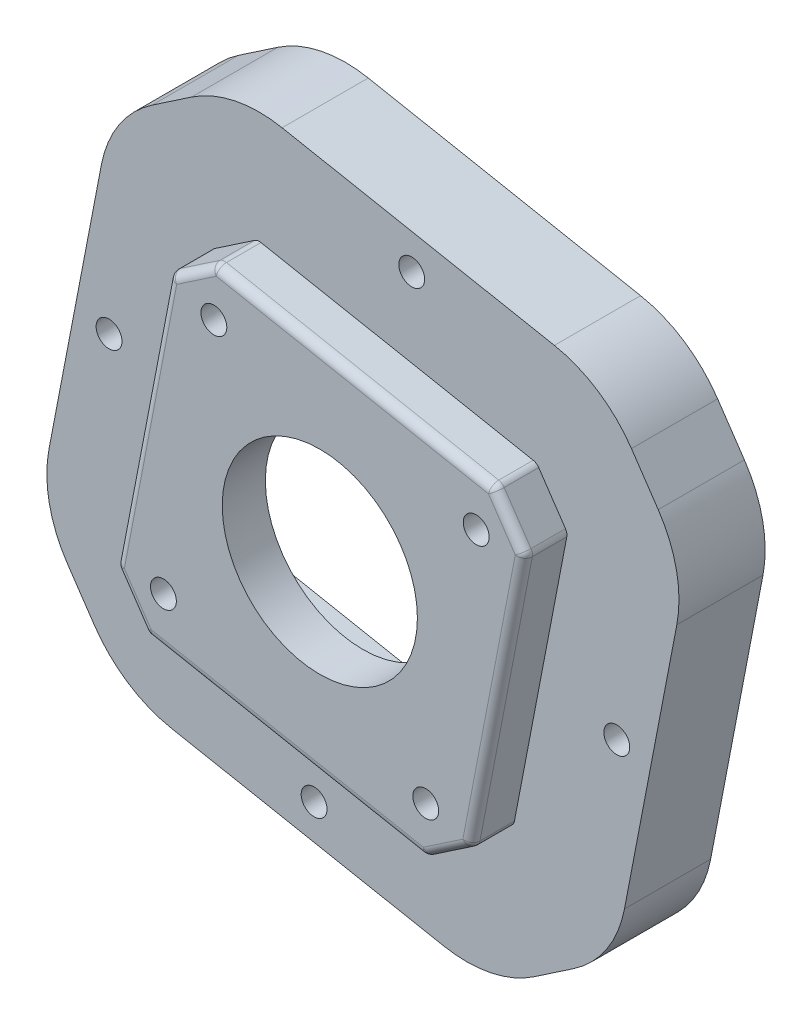
SolidWorks part; units mm, degrees
ref_plane "Plan de face" through (0, 0, 0) normal (0, 0, 1) x (1, 0, 0)
ref_plane "Plan de dessus" through (0, 0, 0) normal (0, 1, 0) x (1, 0, 0)
ref_plane "Plan de droite" through (0, 0, 0) normal (1, 0, 0) x (0, 0, -1)
sketch "Esquisse2" plane through (0, 0, 0) normal (0, 0, 1) x (1, 0, 0)
  line L0 (19.7616, 17.585) -> (-11.8313, 23.6595)
  line L1 (-12.581, 23.5054) -> (-17.1639, 20.4007)
  line L2 (-17.585, 19.7616) -> (-23.6595, -11.8313)
  line L3 (-23.5054, -12.581) -> (-20.4007, -17.1639)
  line L4 (-19.7616, -17.585) -> (11.8313, -23.6595)
  line L5 (12.581, -23.5054) -> (17.1639, -20.4007)
  line L6 (17.585, -19.7616) -> (23.6595, 11.8313)
  line L7 (23.5054, 12.581) -> (20.4007, 17.1639)
  line L8 (30.3512, -22.2162) -> (36.4257, 9.3767)
  line L9 (30.3512, -22.2162) -> (36.4257, 9.3767)
  line L10 (34.2681, 19.8723) -> (31.1634, 24.4552)
  line L11 (34.2681, 19.8723) -> (31.1634, 24.4552)
  line L12 (22.2162, 30.3512) -> (-9.3767, 36.4257)
  line L13 (22.2162, 30.3512) -> (-9.3767, 36.4257)
  line L14 (-19.8723, 34.2681) -> (-24.4552, 31.1634)
  line L15 (-19.8723, 34.2681) -> (-24.4552, 31.1634)
  line L40 (-30.3512, 22.2162) -> (-36.4257, -9.3767)
  line L41 (-30.3512, 22.2162) -> (-36.4257, -9.3767)
  line L42 (-34.2681, -19.8723) -> (-31.1634, -24.4552)
  line L43 (-34.2681, -19.8723) -> (-31.1634, -24.4552)
  line L44 (-22.2162, -30.3512) -> (9.3767, -36.4257)
  line L45 (-22.2162, -30.3512) -> (9.3767, -36.4257)
  line L46 (19.8723, -34.2681) -> (24.4552, -31.1634)
  line L47 (19.8723, -34.2681) -> (24.4552, -31.1634)
  arc A0 (-11.8313, 23.6595) -> (-12.581, 23.5054) centre (-12.0201, 22.6775) ccw
  arc A1 (-17.1639, 20.4007) -> (-17.585, 19.7616) centre (-16.603, 19.5728) ccw
  arc A2 (-23.6595, -11.8313) -> (-23.5054, -12.581) centre (-22.6775, -12.0201) ccw
  arc A3 (-20.4007, -17.1639) -> (-19.7616, -17.585) centre (-19.5728, -16.603) ccw
  arc A4 (11.8313, -23.6595) -> (12.581, -23.5054) centre (12.0201, -22.6775) ccw
  arc A5 (17.1639, -20.4007) -> (17.585, -19.7616) centre (16.603, -19.5728) ccw
  arc A6 (23.6595, 11.8313) -> (23.5054, 12.581) centre (22.6775, 12.0201) ccw
  arc A7 (20.4007, 17.1639) -> (19.7616, 17.585) centre (19.5728, 16.603) ccw
  arc A8 (24.4552, -31.1634) -> (30.3512, -22.2162) centre (16.603, -19.5728) ccw
  arc A9 (24.4552, -31.1634) -> (30.3512, -22.2162) centre (16.603, -19.5728) ccw
  arc A10 (36.4257, 9.3767) -> (34.2681, 19.8723) centre (22.6775, 12.0201) ccw
  arc A11 (36.4257, 9.3767) -> (34.2681, 19.8723) centre (22.6775, 12.0201) ccw
  arc A12 (31.1634, 24.4552) -> (22.2162, 30.3512) centre (19.5728, 16.603) ccw
  arc A13 (31.1634, 24.4552) -> (22.2162, 30.3512) centre (19.5728, 16.603) ccw
  arc A14 (-9.3767, 36.4257) -> (-19.8723, 34.2681) centre (-12.0201, 22.6775) ccw
  arc A15 (-9.3767, 36.4257) -> (-19.8723, 34.2681) centre (-12.0201, 22.6775) ccw
  arc A40 (-24.4552, 31.1634) -> (-30.3512, 22.2162) centre (-16.603, 19.5728) ccw
  arc A41 (-24.4552, 31.1634) -> (-30.3512, 22.2162) centre (-16.603, 19.5728) ccw
  arc A42 (-36.4257, -9.3767) -> (-34.2681, -19.8723) centre (-22.6775, -12.0201) ccw
  arc A43 (-36.4257, -9.3767) -> (-34.2681, -19.8723) centre (-22.6775, -12.0201) ccw
  arc A44 (-31.1634, -24.4552) -> (-22.2162, -30.3512) centre (-19.5728, -16.603) ccw
  arc A45 (-31.1634, -24.4552) -> (-22.2162, -30.3512) centre (-19.5728, -16.603) ccw
  arc A46 (9.3767, -36.4257) -> (19.8723, -34.2681) centre (12.0201, -22.6775) ccw
  arc A47 (9.3767, -36.4257) -> (19.8723, -34.2681) centre (12.0201, -22.6775) ccw
  dimension "D1" = 0
extrude "Boss.-Extru.1" add sketch "Esquisse2" along normal blind 10
sketch "Esquisse4" plane through (0, 0, 0) normal (0, 0, -1) x (-1, 0, 0)
  circle A0 centre (29.4604, 5.6645) radius 1.5
  circle A1 centre (5.6645, -29.4604) radius 1.5
  circle A2 centre (-29.4604, -5.6645) radius 1.5
  circle A3 centre (-5.6645, 29.4604) radius 1.5
extrude "Enlèv. mat.-Extru.1" cut sketch "Esquisse4" against normal through all
sketch "Esquisse5" plane through (0, 0, 10) normal (0, 0, 1) x (1, 0, 0)
  line L0 (17.585, -19.7616) -> (23.6595, 11.8313)
  line L1 (23.5054, 12.581) -> (20.4007, 17.1639)
  line L2 (19.7616, 17.585) -> (-11.8313, 23.6595)
  line L3 (-12.581, 23.5054) -> (-17.1639, 20.4007)
  line L4 (-17.585, 19.7616) -> (-23.6595, -11.8313)
  line L5 (-23.5054, -12.581) -> (-20.4007, -17.1639)
  line L6 (-19.7616, -17.585) -> (11.8313, -23.6595)
  line L7 (12.581, -23.5054) -> (17.1639, -20.4007)
  line L8 (30.3512, -22.2162) -> (36.4257, 9.3767)
  line L9 (34.2681, 19.8723) -> (31.1634, 24.4552)
  line L10 (22.2162, 30.3512) -> (-9.3767, 36.4257)
  line L11 (-19.8723, 34.2681) -> (-24.4552, 31.1634)
  line L12 (-30.3512, 22.2162) -> (-36.4257, -9.3767)
  line L13 (-34.2681, -19.8723) -> (-31.1634, -24.4552)
  line L14 (-22.2162, -30.3512) -> (9.3767, -36.4257)
  line L15 (19.8723, -34.2681) -> (24.4552, -31.1634)
  line L24 (-19.8723, 34.2681) -> (-24.4552, 31.1634) construction
  line L25 (-30.3512, 22.2162) -> (-36.4257, -9.3767) construction
  line L26 (-34.2681, -19.8723) -> (-31.1634, -24.4552) construction
  line L27 (-22.2162, -30.3512) -> (9.3767, -36.4257) construction
  line L28 (19.8723, -34.2681) -> (24.4552, -31.1634) construction
  line L29 (30.3512, -22.2162) -> (36.4257, 9.3767) construction
  line L30 (34.2681, 19.8723) -> (31.1634, 24.4552) construction
  line L31 (22.2162, 30.3512) -> (-9.3767, 36.4257) construction
  arc A0 (17.1639, -20.4007) -> (17.585, -19.7616) centre (16.603, -19.5728) ccw
  arc A1 (23.6595, 11.8313) -> (23.5054, 12.581) centre (22.6775, 12.0201) ccw
  arc A2 (20.4007, 17.1639) -> (19.7616, 17.585) centre (19.5728, 16.603) ccw
  arc A3 (-11.8313, 23.6595) -> (-12.581, 23.5054) centre (-12.0201, 22.6775) ccw
  arc A4 (-17.1639, 20.4007) -> (-17.585, 19.7616) centre (-16.603, 19.5728) ccw
  arc A5 (-23.6595, -11.8313) -> (-23.5054, -12.581) centre (-22.6775, -12.0201) ccw
  arc A6 (-20.4007, -17.1639) -> (-19.7616, -17.585) centre (-19.5728, -16.603) ccw
  arc A7 (11.8313, -23.6595) -> (12.581, -23.5054) centre (12.0201, -22.6775) ccw
  arc A8 (24.4552, -31.1634) -> (30.3512, -22.2162) centre (16.603, -19.5728) ccw
  arc A9 (36.4257, 9.3767) -> (34.2681, 19.8723) centre (22.6775, 12.0201) ccw
  arc A10 (31.1634, 24.4552) -> (22.2162, 30.3512) centre (19.5728, 16.603) ccw
  arc A11 (-9.3767, 36.4257) -> (-19.8723, 34.2681) centre (-12.0201, 22.6775) ccw
  arc A12 (-24.4552, 31.1634) -> (-30.3512, 22.2162) centre (-16.603, 19.5728) ccw
  arc A13 (-36.4257, -9.3767) -> (-34.2681, -19.8723) centre (-22.6775, -12.0201) ccw
  arc A14 (-31.1634, -24.4552) -> (-22.2162, -30.3512) centre (-19.5728, -16.603) ccw
  arc A15 (9.3767, -36.4257) -> (19.8723, -34.2681) centre (12.0201, -22.6775) ccw
  arc A18 (31.1634, 24.4552) -> (22.2162, 30.3512) centre (19.5728, 16.603) ccw
  arc A24 (-24.4552, 31.1634) -> (-30.3512, 22.2162) centre (-16.603, 19.5728) ccw construction
  arc A25 (-36.4257, -9.3767) -> (-34.2681, -19.8723) centre (-22.6775, -12.0201) ccw construction
  arc A26 (-31.1634, -24.4552) -> (-22.2162, -30.3512) centre (-19.5728, -16.603) ccw construction
  arc A27 (9.3767, -36.4257) -> (19.8723, -34.2681) centre (12.0201, -22.6775) ccw construction
  arc A28 (24.4552, -31.1634) -> (30.3512, -22.2162) centre (16.603, -19.5728) ccw construction
  arc A29 (36.4257, 9.3767) -> (34.2681, 19.8723) centre (22.6775, 12.0201) ccw construction
  arc A30 (-9.3767, 36.4257) -> (-19.8723, 34.2681) centre (-12.0201, 22.6775) ccw construction
  circle A31 centre (-12.2945, 18.1479) radius 1.5
  circle A32 centre (-18.1479, -12.2945) radius 1.5
  circle A33 centre (18.1479, 12.2945) radius 1.5
  circle A34 centre (12.2945, -18.1479) radius 1.5
  circle A35 centre (0, 0) radius 11.3229
  line M53 (-11.8313, 23.6595) -> (19.7616, 17.585)
  arc M54 (19.7616, 17.585) -> (20.4007, 17.1639) centre (19.5728, 16.603) cw
  line M55 (20.4007, 17.1639) -> (23.5054, 12.581)
  arc M56 (23.5054, 12.581) -> (23.6595, 11.8313) centre (22.6775, 12.0201) cw
  line M57 (23.6595, 11.8313) -> (17.585, -19.7616)
  arc M58 (17.585, -19.7616) -> (17.1639, -20.4007) centre (16.603, -19.5728) cw
  line M59 (17.1639, -20.4007) -> (12.581, -23.5054)
  arc M60 (12.581, -23.5054) -> (11.8313, -23.6595) centre (12.0201, -22.6775) cw
  line M61 (11.8313, -23.6595) -> (-19.7616, -17.585)
  arc M62 (-19.7616, -17.585) -> (-20.4007, -17.1639) centre (-19.5728, -16.603) cw
  line M63 (-20.4007, -17.1639) -> (-23.5054, -12.581)
  arc M64 (-23.5054, -12.581) -> (-23.6595, -11.8313) centre (-22.6775, -12.0201) cw
  line M65 (-23.6595, -11.8313) -> (-17.585, 19.7616)
  arc M66 (-17.585, 19.7616) -> (-17.1639, 20.4007) centre (-16.603, 19.5728) cw
  line M67 (-17.1639, 20.4007) -> (-12.581, 23.5054)
  arc M68 (-12.581, 23.5054) -> (-11.8313, 23.6595) centre (-12.0201, 22.6775) cw
  dimension "D1" = 0
  dimension "D2" = 13
extrude "Boss.-Extru.2" add sketch "Esquisse5" along normal blind 5 separate body contours M53 M68 M67 M66 M65 M64 M63 M62 M61 M60 M59 M58 M57 M56 M55 M54
fillet "Congé3" radius 1 16 edges at (12.2215, -23.657, 15) (14.8724, -21.953, 15) (17.438, -20.123, 15) (20.6223, -3.9652, 15) (23.657, 12.2215, 15) (21.953, 14.8724, 15) (20.123, 17.438, 15) (3.9652, 20.6223, 15) (-12.2215, 23.657, 15) (-14.8724, 21.953, 15) (-17.438, 20.123, 15) (-20.6223, 3.9652, 15) (-23.657, -12.2215, 15) (-21.953, -14.8724, 15) (-20.123, -17.438, 15) (-3.9652, -20.6223, 15)
